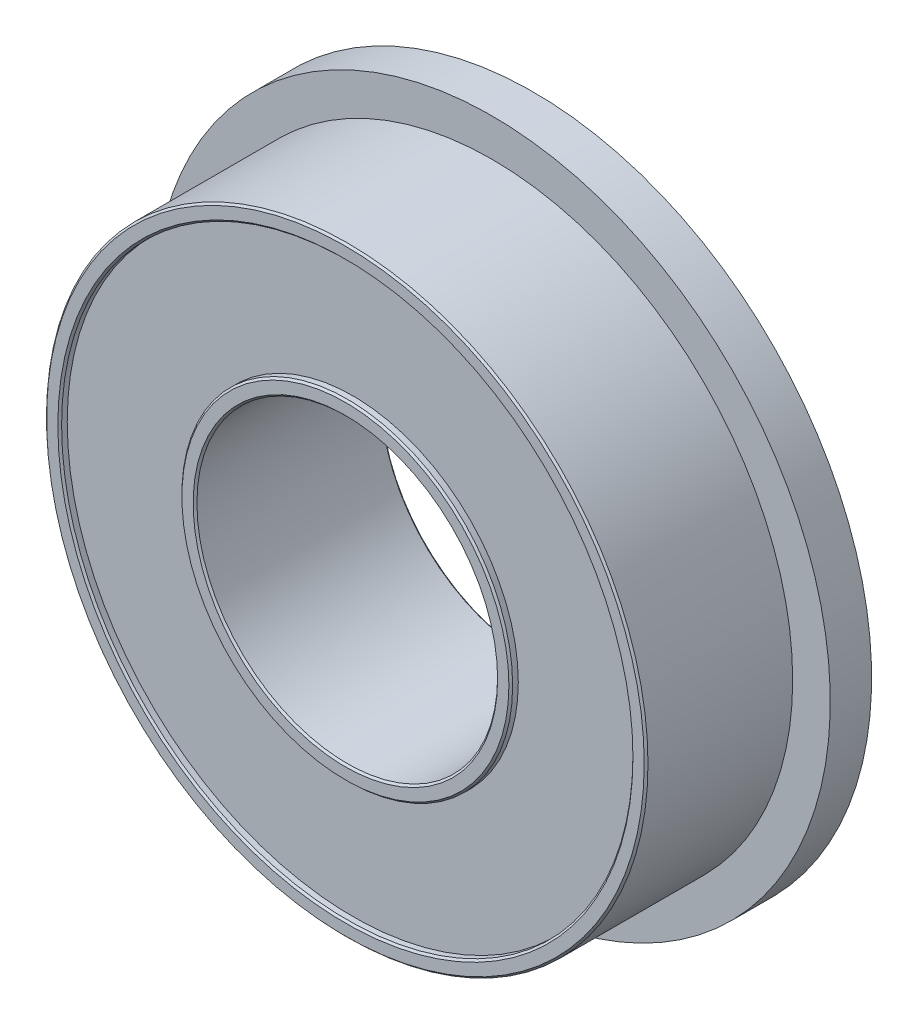
SolidWorks part; units mm, degrees
material "普通碳钢"
ref_plane "前视基准面" through (0, 0, 0) normal (0, 0, 1) x (1, 0, 0)
ref_plane "上视基准面" through (0, 0, 0) normal (0, 1, 0) x (1, 0, 0)
ref_plane "右视基准面" through (0, 0, 0) normal (1, 0, 0) x (0, 0, -1)
sketch "草图1" plane through (0, 0, 0) normal (0, 0, 1) x (1, 0, 0)
  circle A0 centre (0, 0) radius 4
  circle A1 centre (0, 0) radius 8
  dimension "D1" = 8
  dimension "D2" = 16
extrude "凸台-拉伸1" add sketch "草图1" along normal mid plane 5
sketch "草图3" plane through (0, 0, -2.5) normal (0, 0, -1) x (-1, 0, 0)
  circle A0 centre (0, 0) radius 4 construction
  circle A1 centre (0, 0) radius 4
  circle A2 centre (0, 0) radius 9
  dimension "D1" = 18
extrude "凸台-拉伸2" add sketch "草图3" against normal blind 1.1
sketch "草图4" plane through (0, 0, 2.5) normal (0, 0, 1) x (1, 0, 0)
  circle A2 centre (0, 0) radius 4.4
  circle A3 centre (0, 0) radius 4.4
  circle A6 centre (0, 0) radius 7.6
  circle A7 centre (0, 0) radius 7.6
  dimension "D1" = 0.4
  dimension "D2" = 0.4
extrude "切除-拉伸1" cut sketch "草图4" against normal blind 0.2
mirror "镜向1" about plane through (0, 0, 0) normal (0, 0, 1) of "切除-拉伸1"
chamfer "倒角1" distance 0.05 angle 45 7 edges at (4, 0, -2.5) (4.4, 0, -2.5) (4.4, 0, 2.5) (4, 0, 2.5) (8, 0, 2.5) (7.6, 0, 2.5) (7.6, 0, -2.5)
move or copy body "实体-移动/复制3" [suppressed] bodies to move or copy 109
move or copy body "实体-移动/复制1" [suppressed] bodies to move or copy 109
move or copy body "实体-移动/复制2" [suppressed] bodies to move or copy 109
equation "\"内径\"= 2"
equation "\"外径\"= 5"
equation "\"法兰外径\"= 6.1"
equation "\"宽度\"= 2.3"
equation "\"法兰宽度\"= 0.6"
equation "\"D1@草图1\"=\"内径\""
equation "\"D2@草图1\"=\"外径\""
equation "\"D1@草图3\"=\"法兰外径\""
equation "\"D1@凸台-拉伸1\"=\"宽度\""
equation "\"D1@凸台-拉伸2\"=\"法兰宽度\""
